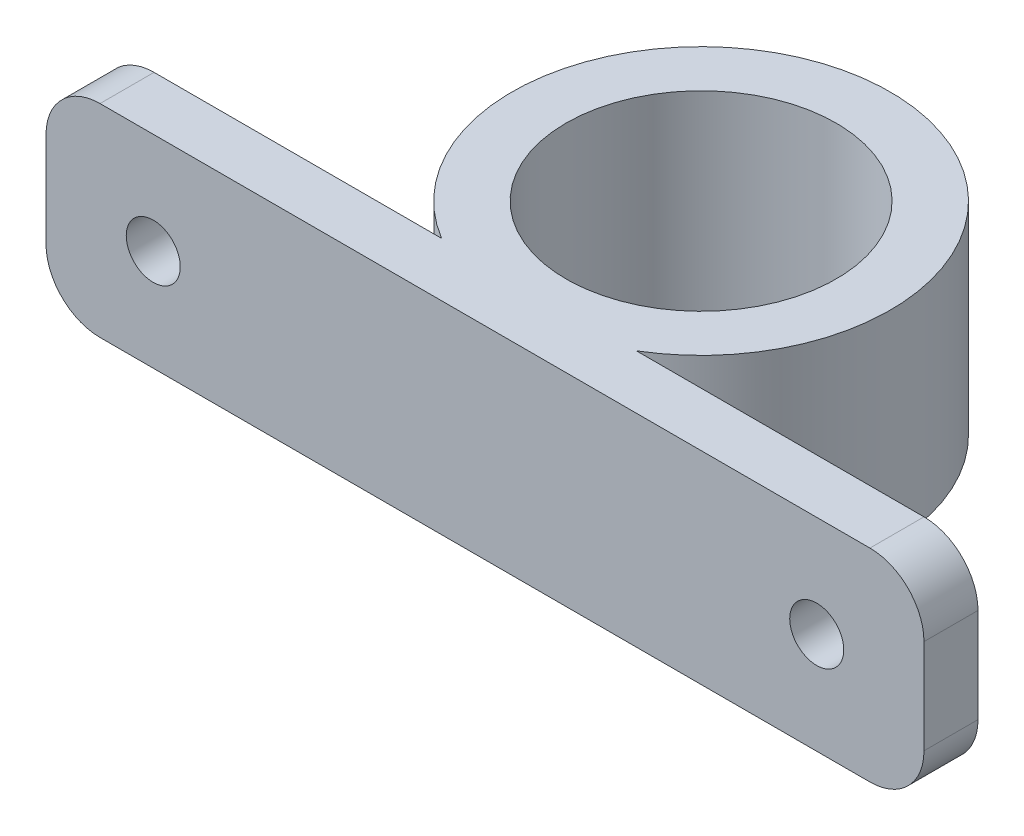
SolidWorks part; units mm, degrees
ref_plane "Front Plane" through (0, 0, 0) normal (0, 0, 1) x (1, 0, 0)
ref_plane "Top Plane" through (0, 0, 0) normal (0, 1, 0) x (1, 0, 0)
ref_plane "Right Plane" through (0, 0, 0) normal (1, 0, 0) x (0, 0, -1)
sketch "Sketch1" plane through (0, 0, 0) normal (0, 0, 1) x (1, 0, 0)
  line L1 (16.25, 3.75) -> (-16.25, 3.75)
  line L2 (16.25, 3.75) -> (16.25, -3.75)
  line L3 (16.25, -3.75) -> (-16.25, -3.75)
  line L4 (-16.25, 3.75) -> (-16.25, -3.75)
  line L5 (16.25, 3.75) -> (-16.25, -3.75) construction
  line L6 (16.25, -3.75) -> (-16.25, 3.75) construction
  point P0 (0, 0)
  dimension "D1" = 32.5
  dimension "D2" = 7.5
extrude "Boss-Extrude1" add sketch "Sketch1" along normal blind 2
sketch "Sketch2" plane through (0, 3.75, 0) normal (0, 1, 0) x (1, 0, 0)
  line L0 (16.25, -2) -> (-16.25, -2) construction
  circle A0 centre (0, 6) radius 5
  circle A1 centre (0, 6) radius 7
  dimension "D1" = 10
  dimension "D2" = 14
  dimension "D3" = 8
extrude "Boss-Extrude2" add sketch "Sketch2" against normal blind 7.5
sketch "Sketch3" plane through (0, 0, 0) normal (0, 0, -1) x (-1, 0, 0)
  line L2 (0, 0) -> (-16.25, 0) construction
  line L3 (-16.25, -3.75) -> (-16.25, 3.75) construction
  circle A0 centre (-12.28, 0) radius 1
  circle A1 centre (12.28, 0) radius 1
  dimension "D1" = 2
  dimension "D2" = 24.56
  dimension "D3" = 12.28
extrude "Cut-Extrude1" cut sketch "Sketch3" against normal blind 3.18
fillet "Fillet1" radius 2 4 edges at (16.25, 3.75, 1) (16.25, -3.75, 1) (-16.25, -3.75, 1) (-16.25, 3.75, 1)
